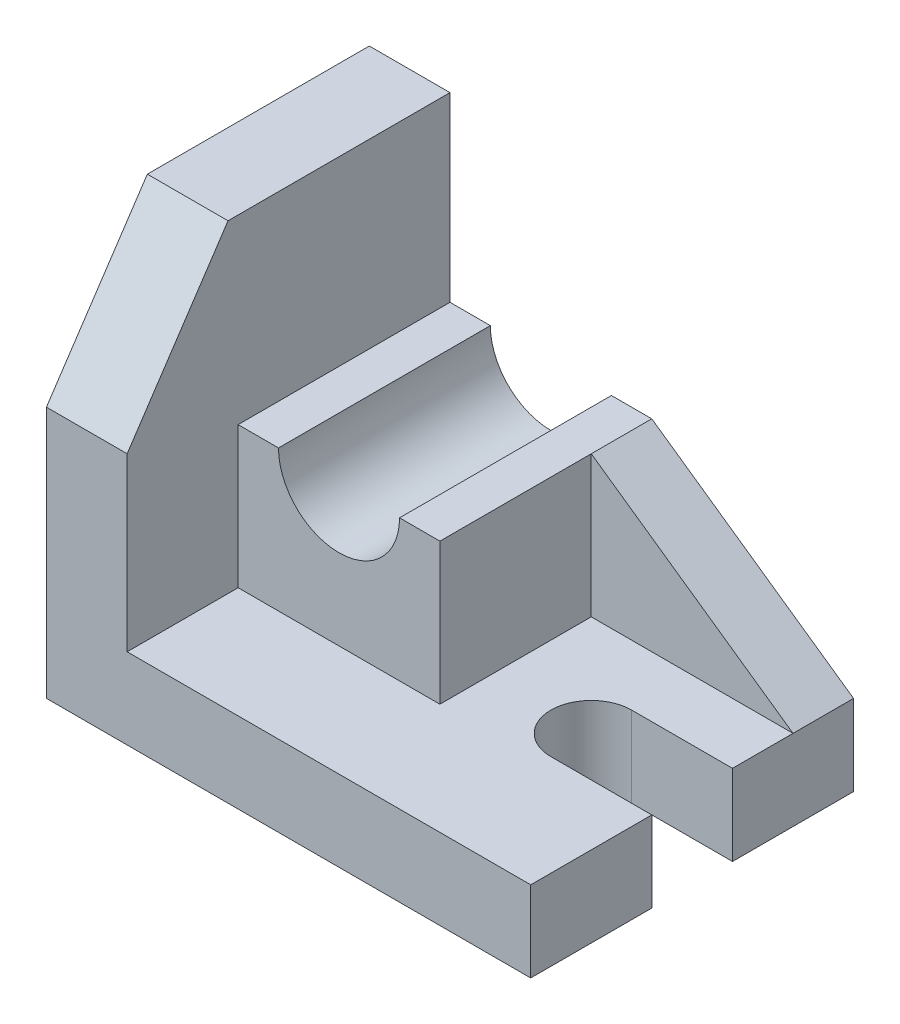
SolidWorks part; units mm, degrees
ref_plane "Front Plane" through (0, 0, 0) normal (0, 0, 1) x (1, 0, 0)
ref_plane "Top Plane" through (0, 0, 0) normal (0, 1, 0) x (1, 0, 0)
ref_plane "Right Plane" through (0, 0, 0) normal (1, 0, 0) x (0, 0, -1)
sketch "Sketch1" plane through (0, 0, 0) normal (0, 1, 0) x (1, 0, 0)
  line L0 (-73.2205, 31.361) -> (22.7795, 31.361)
  line L1 (22.7795, 31.361) -> (22.7795, -32.639)
  line L2 (22.7795, -32.639) -> (-73.2205, -32.639)
  line L3 (-73.2205, -32.639) -> (-73.2205, 31.361)
  dimension "D1" = 96
  dimension "D2" = 64
extrude "Boss-Extrude1" add sketch "Sketch1" along normal blind 16
sketch "Sketch2" plane through (0, 16, 0) normal (0, 1, 0) x (1, 0, 0)
  line L0 (22.7795, -0.639) -> (2.7795, -0.639) construction
  line L1 (22.7795, -32.639) -> (22.7795, 31.361) construction
  line L2 (22.7795, -8.639) -> (2.7795, -8.639)
  line L3 (22.7795, 7.361) -> (2.7795, 7.361)
  line L4 (-73.2205, -32.639) -> (22.7795, -32.639) construction
  arc A0 (22.7795, -8.639) -> (22.7795, 7.361) centre (22.7795, -0.639) ccw
  arc A1 (2.7795, 7.361) -> (2.7795, -8.639) centre (2.7795, -0.639) ccw
  point P4 (12.7795, -0.639)
  dimension "D1" = 24
  dimension "D2" = 20
  dimension "D3" = 16
extrude "Cut-Extrude1" cut sketch "Sketch2" against normal blind 16
sketch "Sketch3" plane through (-73.2205, 0, 0) normal (-1, 0, 0) x (0, 0, 1)
  line L0 (32.639, 16) -> (32.639, 80)
  line L1 (32.639, 80) -> (-31.362, 80)
  line L2 (-31.362, 80) -> (-31.361, 16)
  line L3 (-31.361, 16) -> (32.639, 16)
  dimension "D1" = 64
extrude "Boss-Extrude2" add sketch "Sketch3" against normal blind 16
chamfer "Chamfer1" distance 20 distance2 30 1 edges at (-65.2205, 80, 32.639)
sketch "Sketch5" plane through (0, 0, -31.361) normal (0, 0, -1) x (-1, 0, 0)
  line L0 (57.2205, 16) -> (57.2205, 44)
  line L1 (57.2205, 80) -> (57.2205, 16) construction
  line L2 (57.2205, 44) -> (17.2205, 44)
  line L3 (17.2205, 44) -> (17.2205, 16)
  line L4 (-22.7795, 16) -> (57.2205, 16) construction
  line L5 (17.2205, 16) -> (57.2205, 16)
  dimension "D1" = 28
  dimension "D2" = 40
extrude "Boss-Extrude3" add sketch "Sketch5" against normal blind 42
sketch "Sketch6" plane through (0, 0, 10.639) normal (0, 0, 1) x (1, 0, 0)
  line L0 (-57.2205, 44) -> (-17.2205, 44) construction
  circle A0 centre (-37.2205, 44) radius 12
  dimension "D1" = 24
extrude "Cut-Extrude2" cut sketch "Sketch6" against normal blind 42
sketch "Sketch7" plane through (0, 0, -31.361) normal (0, 0, -1) x (-1, 0, 0)
  line L0 (-22.7795, 16) -> (17.2205, 44)
  line L1 (17.2205, 44) -> (17.2205, 16)
  line L2 (17.2205, 16) -> (-22.7795, 16)
extrude "Boss-Extrude4" add sketch "Sketch7" against normal blind 12
